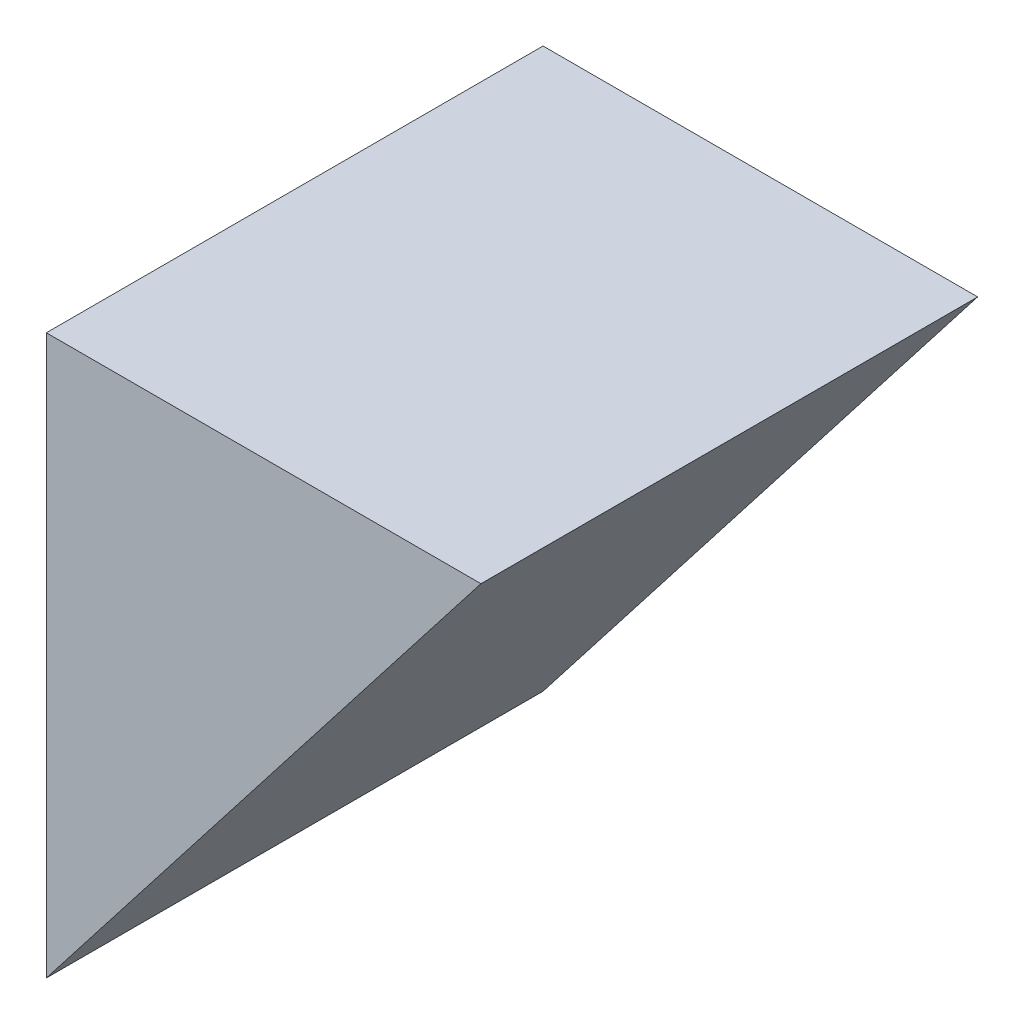
SolidWorks part; units mm, degrees
ref_plane "Front Plane" through (0, 0, 0) normal (0, 0, 1) x (1, 0, 0)
ref_plane "Top Plane" through (0, 0, 0) normal (0, 1, 0) x (1, 0, 0)
ref_plane "Right Plane" through (0, 0, 0) normal (1, 0, 0) x (0, 0, -1)
ref_plane "Plane1" through (0, 0, -20) normal (0, 0, 1) x (1, 0, 0)
sketch "Sketch1" plane through (0, 0, -20) normal (0, 0, 1) x (1, 0, 0)
  line L0 (-8.5773, -13.1481) -> (-8.5773, -22.1481)
  line L1 (-8.5773, -22.1481) -> (-1.5773, -13.1481)
  line L2 (-1.5773, -13.1481) -> (-8.5773, -13.1481)
  dimension "D1" = 9
  dimension "D2" = 7
extrude "Boss-Extrude1" add sketch "Sketch1" along normal mid plane 8
